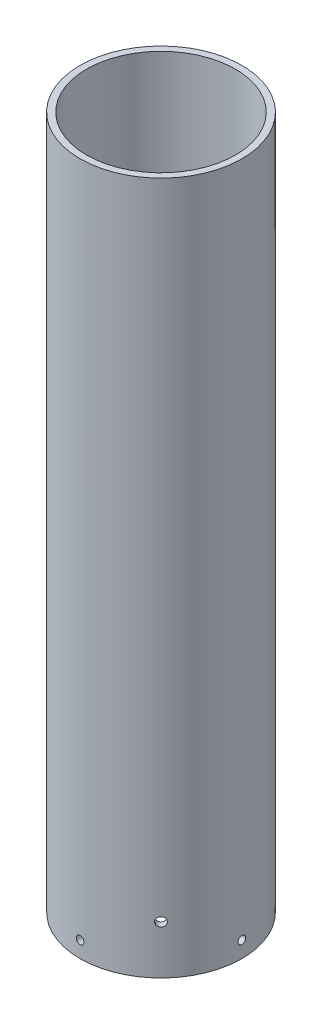
SolidWorks part; units mm, degrees
material "ПВХ 0.007 Смягченный"
ref_plane "Спереди" through (0, 0, 0) normal (0, 0, 1) x (1, 0, 0)
ref_plane "Сверху" through (0, 0, 0) normal (0, 1, 0) x (1, 0, 0)
ref_plane "Справа" through (0, 0, 0) normal (1, 0, 0) x (0, 0, -1)
sketch "Эскиз1" plane through (0, 0, 0) normal (0, 1, 0) x (1, 0, 0)
  circle A0 centre (0, 0) radius 25
  circle A1 centre (0, 0) radius 23
  dimension "ExDBody" = 50
  dimension "InDBody" = 46
extrude "Бобышка-Вытянуть1" add sketch "Эскиз1" along normal blind 214
sketch "Эскиз5" plane through (0, 0, 0) normal (0, 0, 1) x (1, 0, 0)
  circle A0 centre (0, 5) radius 1.2
  dimension "D1" = 2.4
  dimension "D2" = 5
extrude "Вырез-Вытянуть5" cut sketch "Эскиз5" against normal through all
pattern_circular "Круговой массив1" count 4 over 360 about axis through (0, 214, 0) along (0, -1, 0) of "Вырез-Вытянуть5"
ref_plane "Плоскость1" through (0, 0, 0) normal (-0.7071, 0, 0.7071) x (0, -1, 0)
sketch "Эскиз6" plane through (0, 0, 0) normal (-0.7071, 0, 0.7071) x (0, -1, 0)
  line L0 (-214, 0) -> (0, 0) construction
  line L1 (0, -25) -> (0, 25) construction
  circle A0 centre (-15, 0) radius 1.4
  dimension "D1" = 15
extrude "Вырез-Вытянуть6" cut sketch "Эскиз6" against normal through all
pattern_circular "Круговой массив2" count 4 over 360 about axis through (0, 214, 0) along (0, -1, 0) of "Вырез-Вытянуть6"
